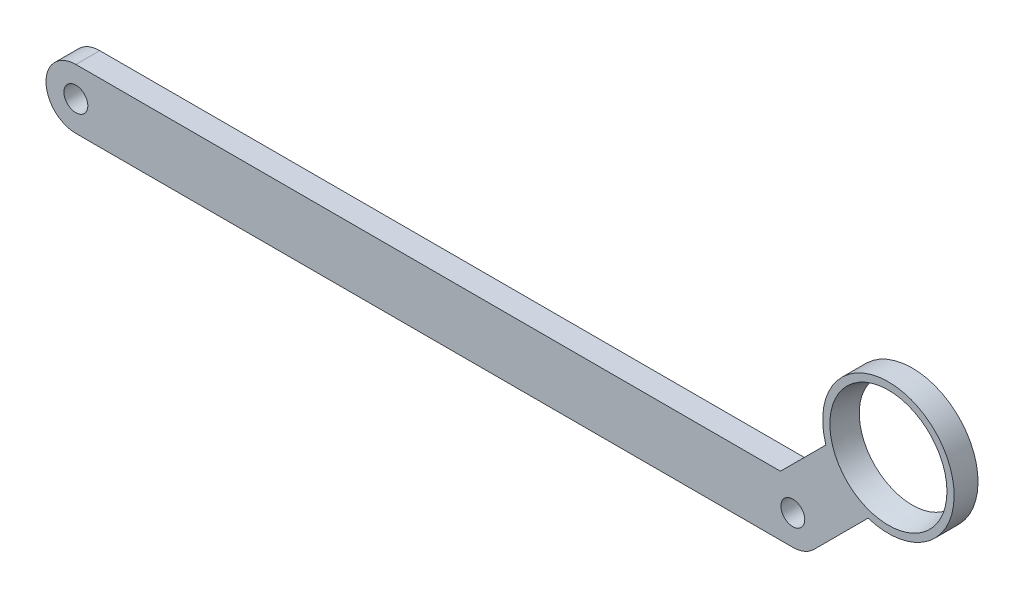
SolidWorks part; units mm, degrees
ref_plane "Front Plane" through (0, 0, 0) normal (0, 0, 1) x (1, 0, 0)
ref_plane "Top Plane" through (0, 0, 0) normal (0, 1, 0) x (1, 0, 0)
ref_plane "Right Plane" through (0, 0, 0) normal (1, 0, 0) x (0, 0, -1)
sketch "Sketch1" plane through (0, 0, 0) normal (0, 0, 1) x (1, 0, 0)
  line L0 (0, -5) -> (0, 5)
  line L1 (75, 5) -> (-75, 5)
  line L2 (75, 5) -> (75, -5)
  line L3 (75, -5) -> (-75, -5)
  line L4 (-75, 5) -> (-75, -5)
  line L5 (74.3363, 4.9558) -> (-75, -5) construction
  line L6 (75, -5) -> (-75, 5) construction
  line L7 (75, 0) -> (75, 5)
  line L10 (75, 0) -> (78.5355, -3.5355)
  line L11 (78.5355, -3.5355) -> (87.6073, 5.5363)
  line L12 (87.6073, 5.5363) -> (80.5363, 12.6073)
  line L13 (80.5363, 12.6073) -> (72.9289, 5)
  line L14 (71.4645, 3.5355) -> (75, 0)
  line L15 (-75, 5) -> (-45, 5)
  line L16 (-45, 5) -> (-45, -5)
  circle A0 centre (-75, 0) radius 5
  circle A1 centre (-75, 0) radius 2
  circle A2 centre (75, 0) radius 5
  circle A3 centre (75, 0) radius 2
  circle A4 centre (91, 16) radius 8.8
  circle A5 centre (91, 16) radius 11
  circle A6 centre (-45, 0) radius 5
  circle A7 centre (-45, 0) radius 2
  point P0 (0, 0)
extrude "Boss-Extrude1" add sketch "Sketch1" along normal blind 4 contours A2 L1 A0 L3 | A3 L2 A2 | A3 L2 A2 | A0 L3 L0 L1 | A3 L2 A2 L14 | A3 L2 A2 L10 | A5 L13 L1 A2 L11 | L12 A5 | L12 A5 A4 | A7 L16 A6 | A7 L16 A6
sketch "Sketch2" plane through (0, 0, 4) normal (0, 0, 1) x (1, 0, 0)
  circle A0 centre (91, 16) radius 9.8
extrude "Cut-Extrude2" cut sketch "Sketch2" against normal blind 4 draft 13
